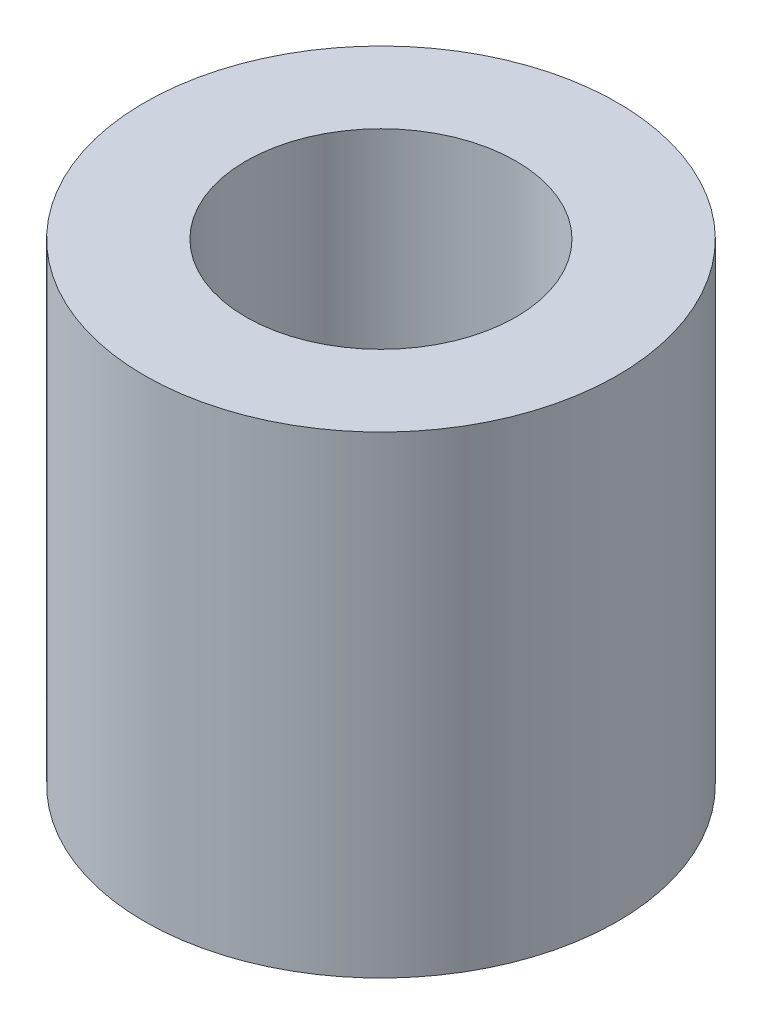
SolidWorks part; units mm, degrees
ref_plane "Front Plane" through (0, 0, 0) normal (0, 0, 1) x (1, 0, 0)
ref_plane "Top Plane" through (0, 0, 0) normal (0, 1, 0) x (1, 0, 0)
ref_plane "Right Plane" through (0, 0, 0) normal (1, 0, 0) x (0, 0, -1)
sketch "Sketch1" plane through (0, 0, 0) normal (0, 1, 0) x (1, 0, 0)
  circle A0 centre (0, 0) radius 100
  circle A1 centre (0, 0) radius 175
  dimension "D1" = 200
  dimension "D2" = 350
extrude "Boss-Extrude1" add sketch "Sketch1" along normal blind 350
scale "Echelle1" bodies to scale 101 scale about centroid uniform scaling yes scale factor 0.47
